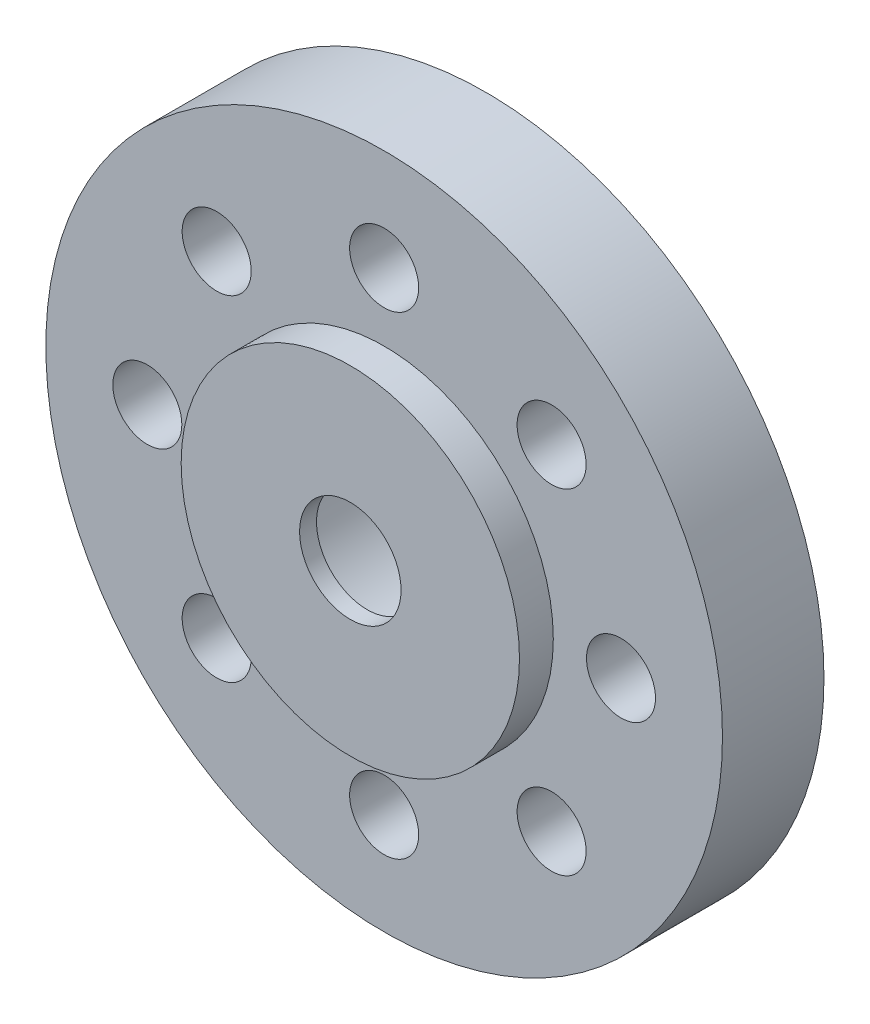
SolidWorks part; units mm, degrees
ref_plane "正面" through (0, 0, 0) normal (0, 0, 1) x (1, 0, 0)
ref_plane "平面" through (0, 0, 0) normal (0, 1, 0) x (1, 0, 0)
ref_plane "右側面" through (0, 0, 0) normal (1, 0, 0) x (0, 0, -1)
sketch "ｽｹｯﾁ1" plane through (0, 0, 0) normal (0, 0, 1) x (1, 0, 0)
  circle A1 centre (-25.029, 61.0503) radius 1.02
  circle A2 centre (-29.9787, 59) radius 1.02
  circle A3 centre (-34.9285, 61.0503) radius 1.02
  circle A4 centre (-36.9787, 66) radius 1.02
  circle A5 centre (-34.9285, 70.9497) radius 1.02
  circle A6 centre (-29.9787, 73) radius 1.02
  circle A7 centre (-25.029, 70.9497) radius 1.02
  circle A8 centre (-22.9787, 66) radius 1.02
  circle A9 centre (-29.9787, 66) radius 10
  circle A11 centre (-29.9787, 66) radius 1.5
  point P23 (-29.9787, 66)
  dimension "D1" = 8
extrude "ﾎﾞｽ - 押し出し1" add sketch "ｽｹｯﾁ1" along normal blind 3
sketch "ｽｹｯﾁ2" plane through (0, 0, 3) normal (0, 0, 1) x (1, 0, 0)
  circle A1 centre (-29.9787, 66) radius 5
extrude "ﾎﾞｽ - 押し出し2" add sketch "ｽｹｯﾁ2" along normal blind 1
sketch "ｽｹｯﾁ3" plane through (0, 0, 3) normal (0, 0, -1) x (-1, 0, 0)
  circle A0 centre (29.9787, 66) radius 3
extrude "ｶｯﾄ - 押し出し1" cut sketch "ｽｹｯﾁ3" against normal blind 0.5 and the other way blind 10
sketch "ｽｹｯﾁ4" plane through (0, 0, 3.5) normal (0, 0, -1) x (-1, 0, 0)
  circle A0 centre (29.9787, 66) radius 1.5
extrude "ｶｯﾄ - 押し出し2" cut sketch "ｽｹｯﾁ4" against normal blind 8.5
